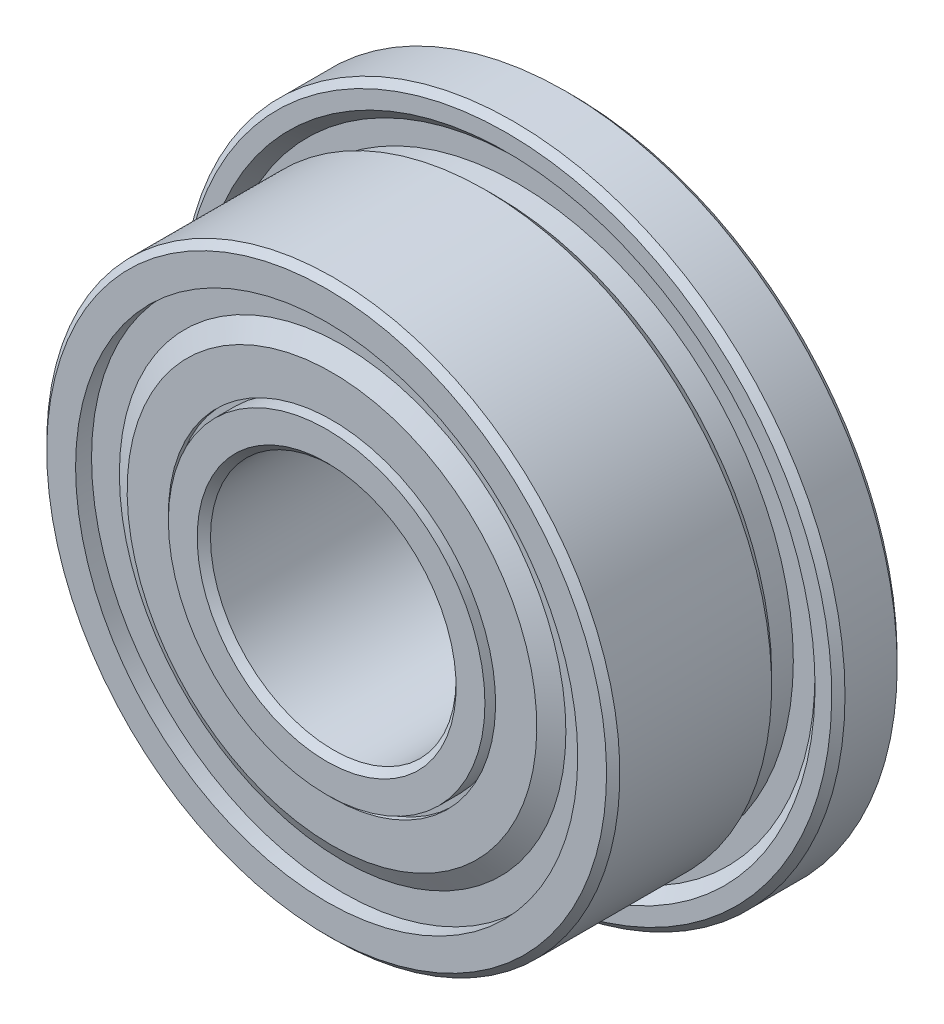
SolidWorks part; units mm, degrees
ref_plane "Front Plane" through (0, 0, 0) normal (0, 0, 1) x (1, 0, 0)
ref_plane "Top Plane" through (0, 0, 0) normal (0, 1, 0) x (1, 0, 0)
ref_plane "Right Plane" through (0, 0, 0) normal (1, 0, 0) x (0, 0, -1)
sketch "Sketch1" plane through (0, 0, 0) normal (1, 0, 0) x (0, 0, -1)
  line L0 (0, 3.5) -> (0, -3.5) construction
  line L1 (-1.5, 3.5) -> (1.5, 3.5) construction
  line L2 (0, 0) -> (1.5, 0) construction
  line L3 (1.5, 4.05) -> (1.5, -4.05) construction
  line L4 (1.5, -4.05) -> (0.7, -4.05) construction
  line L5 (1.5, 1.5) -> (0, 1.5) construction
  line L6 (1.5, 1.5) -> (1.5, -1.5) construction
  dimension "OD" = 7
  dimension "Width" = 3
  dimension "Flange Thickness" = 0.8
  dimension "ID" = 3
  dimension "Flange OD" = 8.1
sketch "Sketch2" plane through (0, 0, 0) normal (1, 0, 0) x (0, 0, -1)
  line L0 (1.5, 4.05) -> (0.7, 4.05)
  line L1 (0.7, 4.05) -> (0.7, 3.7652)
  line L2 (0.4348, 3.5) -> (-1.5, 3.5)
  line L3 (-1.5, 3.5) -> (-1.5, 2.85)
  line L4 (-1.5, 2.85) -> (-0.3571, 2.85)
  line L5 (1.5, 4.05) -> (1.5, -4.05) construction
  line L6 (1.5, 2.85) -> (1.5, 4.05)
  line L7 (1.5, 1.5) -> (-1.5, 1.5)
  line L8 (-1.5, 1.5) -> (-1.5, 2.15)
  line L9 (-1.5, 2.15) -> (-0.3571, 2.15)
  line L10 (1.5, 2.15) -> (1.5, 1.5)
  line L11 (0, 3.5) -> (0, 1.5) construction
  line L12 (-0.5, 2.5) -> (0.5, 2.5) construction
  line L13 (0.3571, 2.85) -> (1.5, 2.85)
  line L14 (0.3571, 2.15) -> (1.5, 2.15)
  line L15 (0.7, 3.7652) -> (0.8326, 3.6326)
  line L16 (0.8326, 3.6326) -> (0.8326, 3.3674)
  line L17 (0.8326, 3.3674) -> (0.5674, 3.3674)
  line L18 (0.5674, 3.3674) -> (0.4348, 3.5)
  line L19 (0.7, 3.5) -> (0.8326, 3.3674) construction
  line L20 (0.8326, 3.6326) -> (0.5674, 3.3674) construction
  line L21 (0.4348, 3.5) -> (0.7, 3.5) construction
  line L22 (0.7, 3.5) -> (0.7, 3.7652) construction
  line L23 (-1.5, 0) -> (1.5, 0) construction
  circle A0 centre (0, 2.5) radius 0.5 construction
  arc A1 (-0.3571, 2.85) -> (0.3571, 2.85) centre (0, 2.5) cw
  arc A2 (-0.3571, 2.15) -> (0.3571, 2.15) centre (0, 2.5) ccw
  dimension "Ball Dia." = 1
  dimension "D2" = 135
  dimension "D3" = 0.375
  dimension "Race Thikness" = 0.65
  dimension "D4" = 0.7
revolve "Revolve1" add sketch "Sketch2" angle 360 about L2
fillet "Fillet1" radius 0.0813 3 edges at (0, -4.05, -1.5) (0, -4.05, -0.7) (0, -3.5, 1.5) profile chamfer
sketch "Sketch3" plane through (0, 0, 0) normal (0, 0, 1) x (1, 0, 0)
  line L0 (-1.5, 0) -> (1.5, 0) construction
  line L1 (-3.5, 0) -> (3.5, 0) construction
  point P5 (0, 0)
  dimension "ID2" = 3
  dimension "OD2" = 7
fillet "Fillet2" radius 0.0813 2 edges at (0, -1.5, -1.5) (0, -1.5, 1.5) profile chamfer
sketch "Sketch7" plane through (0, 0, 0) normal (0, 0, 1) x (1, 0, 0)
  line L0 (0, 3) -> (0, 2)
  line L1 (0, 4.05) -> (0, -4.05) construction
  line L2 (-0.6124, 3) -> (0, 0) construction
  line L3 (0, 0) -> (0.6124, 3) construction
  line L4 (0.6124, 3) -> (-0.6124, 3) construction
  circle A0 centre (0, 2.5) radius 0.5 construction
  circle A1 centre (0, 0) radius 3 construction
  circle A2 centre (0, 0) radius 2 construction
  arc A4 (0, 3) -> (0, 2) centre (0, 2.5) ccw
  dimension "D1" = 23.074
revolve "Revolve3" add sketch "Sketch7" angle 360 about L0
pattern_circular "CirPattern3" count 12 over 360 about axis through (0, 0, 0) along (0, 0, 1) of bodies 107
sketch "Sketch8" plane through (0, 0, 0) normal (1, 0, 0) x (0, 0, -1)
  line L1 (-1.5, 2.85) -> (-1.24, 2.85)
  line L2 (-1.5, 2.85) -> (-1.5, 3.0667)
  line L3 (-1.5, 3.0667) -> (-1.24, 3.0667)
  line L4 (-1.24, 2.85) -> (-1.24, 3.0667)
  line L5 (1.5, 2.85) -> (1.24, 2.85)
  line L6 (1.5, 2.85) -> (1.5, 3.0667)
  line L7 (1.5, 3.0667) -> (1.24, 3.0667)
  line L8 (1.24, 2.85) -> (1.24, 3.0667)
  line L9 (1.5, 2.15) -> (1.24, 2.15)
  line L10 (1.5, 2.15) -> (1.5, 1.9333)
  line L11 (1.5, 1.9333) -> (1.24, 1.9333)
  line L12 (1.24, 2.15) -> (1.24, 1.9333)
  line L13 (-1.5, 2.15) -> (-1.24, 2.15)
  line L14 (-1.5, 2.15) -> (-1.5, 1.9333)
  line L15 (-1.5, 1.9333) -> (-1.24, 1.9333)
  line L16 (-1.24, 2.15) -> (-1.24, 1.9333)
  dimension "D1" = 0.2167
  dimension "D2" = 0.26
revolve "Cut-Revolve1" cut sketch "Sketch8" angle 360 about L2
sketch "Sketch9" plane through (0, 0, 0) normal (1, 0, 0) x (0, 0, -1)
  line L0 (-1.24, 3.0667) -> (-1.24, 2.7095)
  line L1 (-1.24, 2.7095) -> (-1.37, 2.4844)
  line L2 (-1.37, 2.4844) -> (-1.37, 1.9983)
  line L3 (1.37, 1.9983) -> (1.37, 1.9333) construction
  line L4 (1.24, 3.0667) -> (1.24, 2.7095)
  line L5 (1.24, 2.7095) -> (1.37, 2.4844)
  line L6 (1.37, 2.4844) -> (1.37, 1.9983)
  line L7 (1.5, 1.9333) -> (1.24, 1.9333) construction
  line L8 (-1.305, 3.0667) -> (-1.305, 2.7269)
  line L9 (-1.305, 2.7269) -> (-1.435, 2.5018)
  line L10 (-1.435, 2.5018) -> (-1.435, 1.9983)
  line L11 (-1.24, 3.0667) -> (-1.305, 3.0667)
  line L12 (-1.37, 1.9983) -> (-1.435, 1.9983)
  line L13 (1.305, 3.0667) -> (1.305, 2.7269)
  line L14 (1.305, 2.7269) -> (1.435, 2.5018)
  line L15 (1.435, 2.5018) -> (1.435, 1.9983)
  line L16 (1.24, 3.0667) -> (1.305, 3.0667)
  line L17 (1.37, 1.9983) -> (1.435, 1.9983)
  line L18 (-1.24, 2.7095) -> (-1.24, 2.5308) construction
  line L19 (1.24, 2.7095) -> (1.24, 3.0667) construction
  line L20 (-1.24, 1.9333) -> (-1.5, 1.9333) construction
  line L22 (-1.37, 1.9983) -> (-1.37, 1.9333) construction
  dimension "D2" = 150
  dimension "D1" = 150
  dimension "D5" = 0.26
  dimension "D3" = 0.065
  dimension "D4" = 0.065
  dimension "D6" = 0.3571
revolve "Revolve4" add sketch "Sketch9" angle 360 about L2
equation "\"D1@Fillet1\"=\"Race Thikness@Sketch2\"/8"
equation "\"ID2@Sketch3\" = \"ID@Sketch1\""
equation "\"OD2@Sketch3\" = \"OD@Sketch1\""
equation "\"D1@Fillet2\"=\"Race Thikness@Sketch2\"/8"
equation "\"D1@CirPattern3\"=360/\"D1@Sketch7\"-4"
equation "\"D1@Sketch8\"=\"Race Thikness@Sketch2\"/3"
equation "\"D2@Sketch8\"=\"Race Thikness@Sketch2\"/2.5"
equation "\"D3@Sketch9\"=\"D5@Sketch9\"/4"
equation "\"D4@Sketch9\"=\"D5@Sketch9\"/4"
equation "\"D1@Sketch9\"=\"D2@Sketch9\""
equation "\"Ball Dia.@Sketch2\" = \"D1@Sketch2\"*.5"
equation "\"D4@Sketch2\"=((\"OD@Sketch1\"-\"ID@Sketch1\")/2)*.35"
